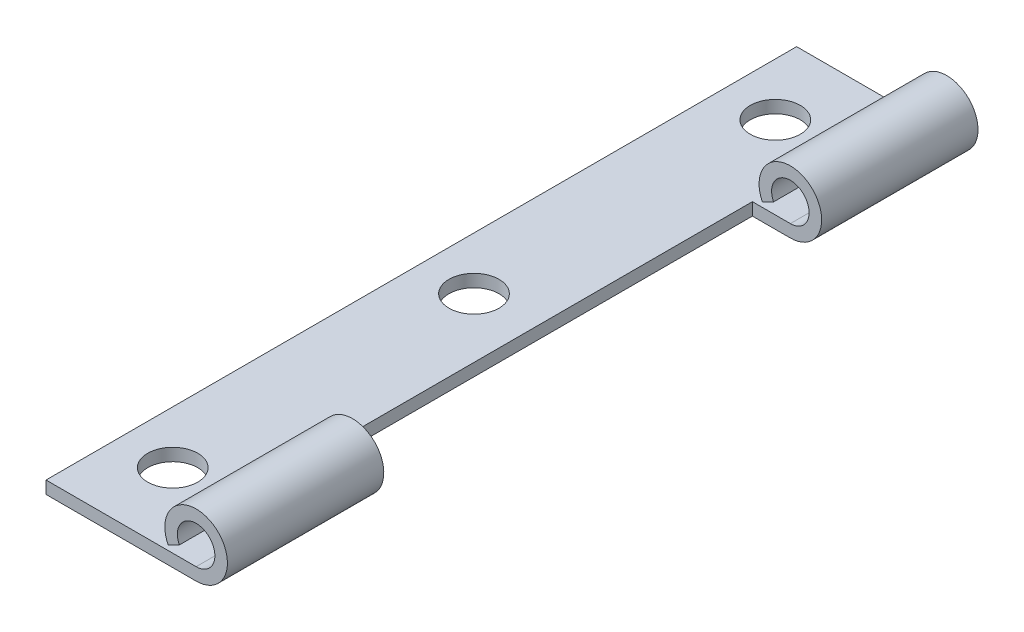
SolidWorks part; units mm, degrees
ref_plane "Front Plane" through (0, 0, 0) normal (0, 0, 1) x (1, 0, 0)
ref_plane "Top Plane" through (0, 0, 0) normal (0, 1, 0) x (1, 0, 0)
ref_plane "Right Plane" through (0, 0, 0) normal (1, 0, 0) x (0, 0, -1)
sketch "Sketch1" plane through (0, 0, 0) normal (0, 0, 1) x (1, 0, 0)
  line L0 (0, 0) -> (12, 0)
  arc A0 (12, 0) -> (9.7624, 1.385) centre (12, 2.5) ccw
sketch "Sketch3" plane through (0, 0, 0) normal (1, 0, 0) x (0, 0, -1)
  line L1 (0, 0) -> (-60, 0)
  line L2 (0, 0) -> (0, 1)
  line L3 (0, 1) -> (-60, 1)
  line L4 (-60, 0) -> (-60, 1)
sweep "Sweep1" add profiles "Sketch3" path "Sketch1"
sketch "Sketch4" plane through (0, 0, 0) normal (0, -1, 0) x (-1, 0, 0)
  line L0 (0, -30) -> (-29.3061, -30) construction
  line L2 (-12, -60) -> (-12, 0) construction
  line L3 (-8.9646, -47.5) -> (-15.0354, -47.5)
  line L4 (-8.9646, -47.5) -> (-8.9646, -12.5)
  line L5 (-8.9646, -12.5) -> (-15.0354, -12.5)
  line L6 (-15.0354, -47.5) -> (-15.0354, -12.5)
  line L7 (-8.9646, -47.5) -> (-15.0354, -12.5) construction
  line L8 (-8.9646, -12.5) -> (-15.0354, -47.5) construction
  point P1 (-12, -30)
extrude "Cut-Extrude1" cut sketch "Sketch4" against normal through all
sketch "Sketch5" plane through (0, 1, 0) normal (0, 1, 0) x (1, 0, 0)
  line L0 (8.9646, -30) -> (23.6331, -30) construction
  circle A0 centre (4.2129, -5.9173) radius 2
  circle A1 centre (4.2129, -54.0827) radius 2
  circle A2 centre (4.2129, -30) radius 2
extrude "Cut-Extrude2" cut sketch "Sketch5" against normal through all
